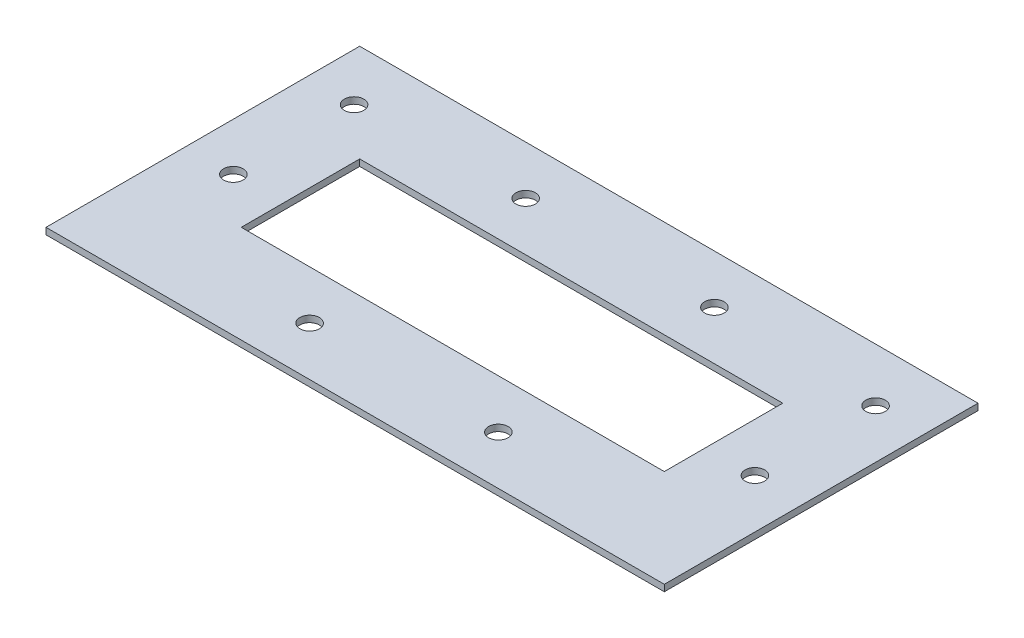
SolidWorks part; units mm, degrees
ref_plane "Front" through (0, 0, 0) normal (0, 0, 1) x (1, 0, 0)
ref_plane "Top" through (0, 0, 0) normal (0, 1, 0) x (1, 0, 0)
ref_plane "Right" through (0, 0, 0) normal (1, 0, 0) x (0, 0, -1)
sketch "Sketch2" plane through (0, 0, 0) normal (0, 1, 0) x (1, 0, 0)
  line L0 (-32.5, 24.0987) -> (-32.5, 9.0987) construction
  line L1 (-47.5, -24.0987) -> (47.5, -24.0987)
  line L2 (-47.5, -24.0987) -> (-47.5, 24.0987)
  line L3 (-47.5, 24.0987) -> (47.5, 24.0987)
  line L4 (47.5, -24.0987) -> (47.5, 24.0987)
  line L5 (-47.5, -24.0987) -> (47.5, 24.0987) construction
  line L6 (-47.5, 24.0987) -> (47.5, -24.0987) construction
  line L7 (-32.5, -9.0987) -> (32.5, -9.0987)
  line L8 (-32.5, -9.0987) -> (-32.5, 9.0987)
  line L9 (-32.5, 9.0987) -> (32.5, 9.0987)
  line L10 (32.5, -9.0987) -> (32.5, 9.0987)
  line L11 (-32.5, -9.0987) -> (32.5, 9.0987) construction
  line L12 (-32.5, 9.0987) -> (32.5, -9.0987) construction
  line L13 (32.5, 9.0987) -> (32.5, 24.0987) construction
  line L14 (-32.5, 16.5987) -> (32.5, 16.5987) construction
  line L15 (32.5, 9.0987) -> (47.5, 9.0987) construction
  line L16 (32.5, -9.0987) -> (47.5, -9.0987) construction
  line L17 (39.9789, 24.0987) -> (39.9789, -24.0987) construction
  line L18 (-47.5, 9.0987) -> (-32.5, 9.0987) construction
  line L19 (-47.5, -9.0987) -> (-32.5, -9.0987) construction
  line L20 (-32.5, -9.0987) -> (-32.5, -24.0987) construction
  line L21 (32.5, -9.0987) -> (32.5, -24.0987) construction
  line L22 (-40.149, 24.0987) -> (-40.149, -24.0987) construction
  line L23 (-32.5, -16.5987) -> (32.5, -16.5987) construction
  circle A0 centre (-14.5, 16.5987) radius 1.5
  circle A1 centre (14.5, 16.5987) radius 1.5
  circle A2 centre (-40.149, 15.8818) radius 1.5
  circle A3 centre (-40.149, -2.6627) radius 1.5
  circle A4 centre (39.9789, 15.8818) radius 1.5
  circle A5 centre (39.9789, -2.6627) radius 1.5
  circle A6 centre (-14.5, -16.5987) radius 1.5
  circle A7 centre (14.5, -16.5987) radius 1.5
  point P0 (0, 0)
  point P6 (0, 0)
  dimension "D7" = 18
  dimension "D8" = 18
  dimension "D1" = 48.1974
  dimension "D2" = 15
  dimension "D3" = 15
  dimension "D4" = 15
  dimension "D5" = 15
  dimension "D6" = 95
extrude "Boss-Extrude2" add sketch "Sketch2" along normal blind 1
